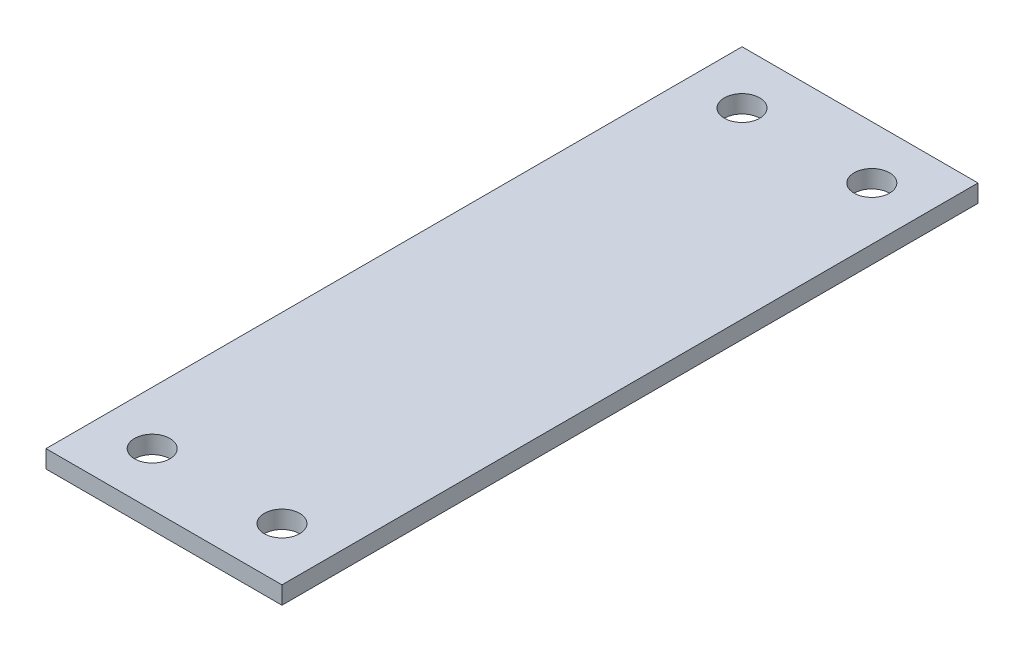
SolidWorks part; units mm, degrees
ref_plane "前视基准面" through (0, 0, 0) normal (0, 0, 1) x (1, 0, 0)
ref_plane "上视基准面" through (0, 0, 0) normal (0, 1, 0) x (1, 0, 0)
ref_plane "右视基准面" through (0, 0, 0) normal (1, 0, 0) x (0, 0, -1)
sketch "草图1" plane through (0, 0, 0) normal (0, 1, 0) x (1, 0, 0)
  line L1 (-10, 29.5) -> (10, 29.5)
  line L2 (-10, 29.5) -> (-10, -29.5)
  line L3 (-10, -29.5) -> (10, -29.5)
  line L4 (10, 29.5) -> (10, -29.5)
  line L5 (-10, 29.5) -> (10, -29.5) construction
  line L6 (-10, -29.5) -> (10, 29.5) construction
  point P0 (0, 0)
  dimension "D1" = 20
  dimension "D2" = 59
extrude "凸台-拉伸1" add sketch "草图1" along normal blind 1.5
sketch "草图4" plane through (0, 0, 0) normal (0, -1, 0) x (1, 0, 0)
  line L0 (-10, 29.5) -> (-5.5, 29.5)
  line L1 (-10, 29.5) -> (10, 29.5) construction
  line L2 (-5.5, 29.5) -> (-5.5, 25)
  line L3 (-10, -29.5) -> (-5.5, -29.5)
  line L4 (10, -29.5) -> (-10, -29.5) construction
  line L5 (-5.5, -29.5) -> (-5.5, -25)
  line L6 (-5.5, 25) -> (5.5, 25)
  line L7 (-5.5, -25) -> (5.5, -25)
  circle A0 centre (-5.5, 25) radius 1.5
  circle A1 centre (-5.5, -25) radius 1.5
  circle A2 centre (5.5, 25) radius 1.5
  circle A3 centre (5.5, -25) radius 1.5
  dimension "D5" = 3
  dimension "D6" = 3
  dimension "D8" = 3
  dimension "D10" = 3
  dimension "D1" = 4.5
  dimension "D2" = 4.5
  dimension "D3" = 4.5
  dimension "D4" = 4.5
  dimension "D7" = 11
  dimension "D9" = 11
hole_wizard "M3 螺纹孔1" positions "3D草图1" profile "草图5" tap size "M3" standard "ISO" end condition through all
sketch3d "3D草图1"
  point P0 (-5.5, 0, 25)
  point P3 (5.5, 0, 25)
  point P6 (-5.5, 0, -25)
  point P9 (5.5, 0, -25)
sketch "草图5" plane through (-5.5, 0, 25) normal (1, 0, 0) x (0, 0, -1)
  line L0 (0, 0) -> (0, 1.5)
  line L1 (0, 1.5) -> (1.5, 1.5)
  line L2 (1.5, 1.5) -> (1.5, 0)
  line L5 (1.5, 0) -> (0, 0)
  line L11 (0, -6.35) -> (0, 107.95) construction
  dimension "通孔螺纹孔钻头直径" = 3
  dimension "通孔螺纹孔钻头深度" = 1.5
cosmetic thread "孔螺蚊线1"
cosmetic thread "孔螺蚊线2"
cosmetic thread "孔螺蚊线3"
cosmetic thread "孔螺蚊线4"
